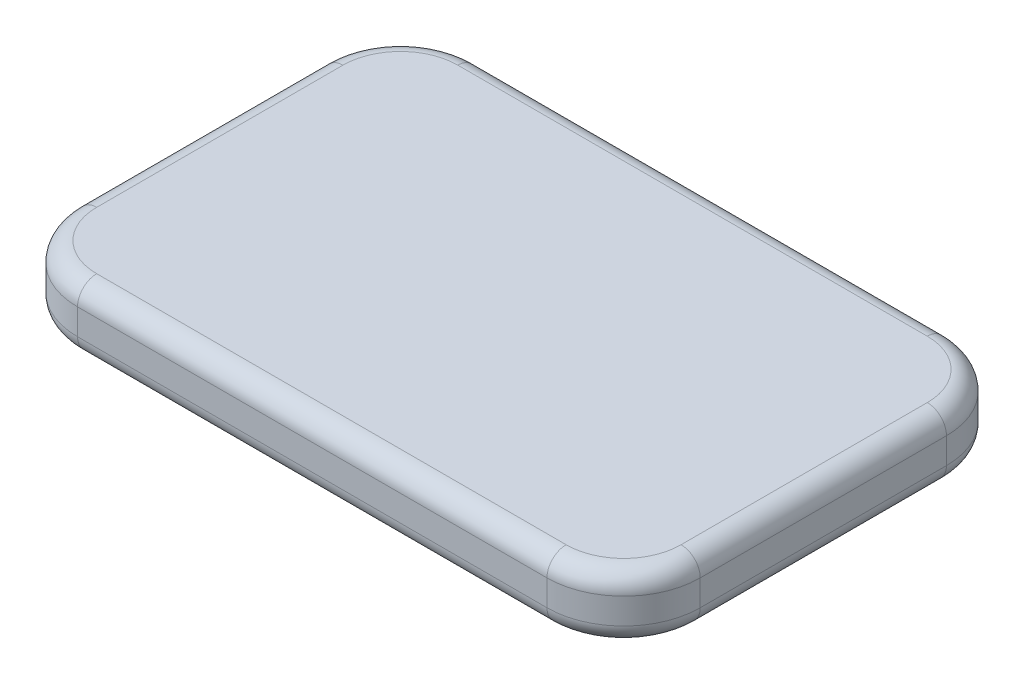
SolidWorks part; units mm, degrees
ref_plane "Front Plane" through (0, 0, 0) normal (0, 0, 1) x (1, 0, 0)
ref_plane "Top Plane" through (0, 0, 0) normal (0, 1, 0) x (1, 0, 0)
ref_plane "Right Plane" through (0, 0, 0) normal (1, 0, 0) x (0, 0, -1)
sketch "Sketch2" plane through (0, 0, 0) normal (0, 1, 0) x (1, 0, 0)
  line L1 (0, 0) -> (165.1, 0)
  line L2 (0, 0) -> (0, 105.918)
  line L3 (0, 105.918) -> (165.1, 105.918)
  line L4 (165.1, 0) -> (165.1, 105.918)
  dimension "D1" = 165.1
  dimension "D2" = 105.918
extrude "Boss-Extrude1" add sketch "Sketch2" along normal blind 17.018 contours L2 L1 L4 L3
fillet "Fillet1" radius 20.32 4 edges at (165.1, 8.509, 0) (165.1, 8.509, -105.918) (0, 8.509, -105.918) (0, 8.509, 0)
fillet "Fillet2" radius 5.08 8 edges at (5.9516, 17.018, -5.9516) (82.55, 17.018, 0) (159.1484, 17.018, -5.9516) (165.1, 17.018, -52.959) (159.1484, 17.018, -99.9664) (82.55, 17.018, -105.918) (5.9516, 17.018, -99.9664) (0, 17.018, -52.959)
fillet "Fillet3" radius 5.08 8 edges at (5.9516, 0, -5.9516) (82.55, 0, 0) (159.1484, 0, -5.9516) (165.1, 0, -52.959) (159.1484, 0, -99.9664) (82.55, 0, -105.918) (5.9516, 0, -99.9664) (0, 0, -52.959)
